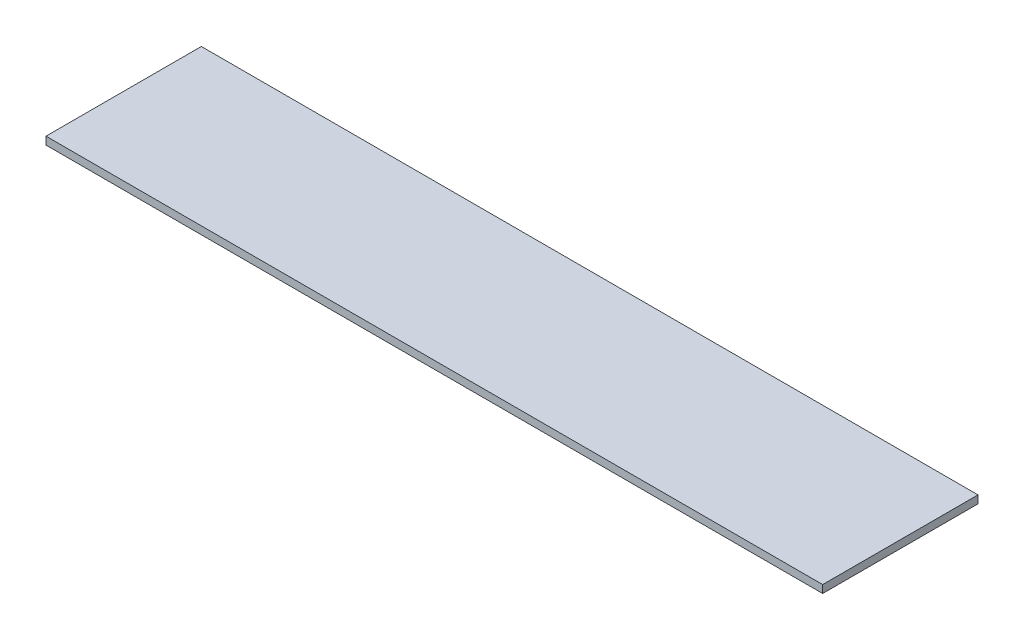
SolidWorks part; units mm, degrees
ref_plane "Alzado" through (0, 0, 0) normal (0, 0, 1) x (1, 0, 0)
ref_plane "Planta" through (0, 0, 0) normal (0, 1, 0) x (1, 0, 0)
ref_plane "Vista lateral" through (0, 0, 0) normal (1, 0, 0) x (0, 0, -1)
sketch "Croquis1" plane through (0, 0, 0) normal (0, 1, 0) x (1, 0, 0)
  line L1 (-900, 180) -> (900, 180)
  line L2 (-900, 180) -> (-900, -180)
  line L3 (-900, -180) -> (900, -180)
  line L4 (900, 180) -> (900, -180)
  line L5 (-900, 180) -> (900, -180) construction
  line L6 (-900, -180) -> (900, 180) construction
  point P0 (0, 0)
  dimension "D1" = 1800
  dimension "D2" = 360
extrude "Saliente-Extruir1" add sketch "Croquis1" along normal blind 18
